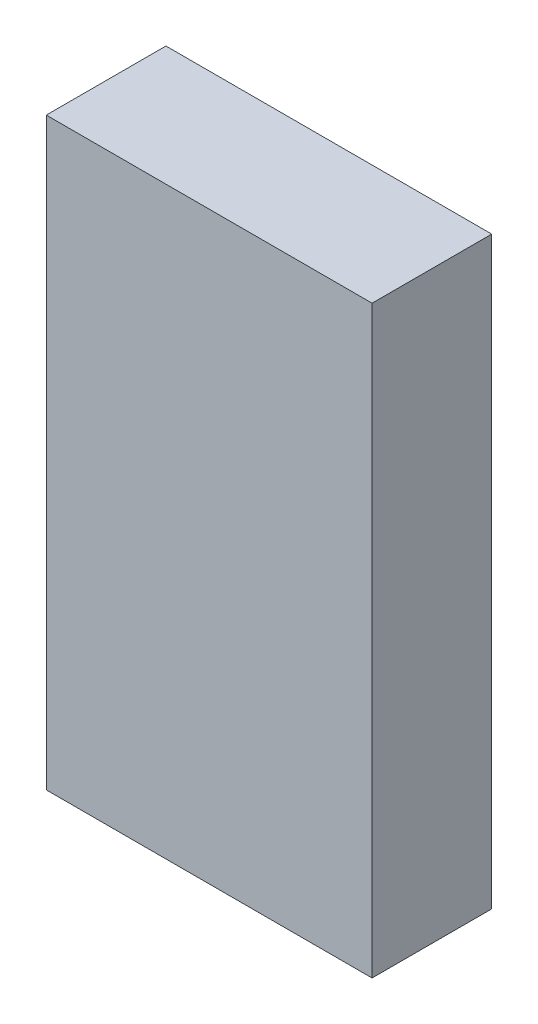
SolidWorks part; units mm, degrees
ref_plane "Спереди" through (0, 0, 0) normal (0, 0, 1) x (1, 0, 0)
ref_plane "Сверху" through (0, 0, 0) normal (0, 1, 0) x (1, 0, 0)
ref_plane "Справа" through (0, 0, 0) normal (1, 0, 0) x (0, 0, -1)
sketch "Эскиз1" plane through (0, 0, 0) normal (0, 0, 1) x (1, 0, 0)
  line L1 (-13.6143, 24.4221) -> (13.6143, 24.4221)
  line L2 (-13.6143, 24.4221) -> (-13.6143, -24.4221)
  line L3 (-13.6143, -24.4221) -> (13.6143, -24.4221)
  line L4 (13.6143, 24.4221) -> (13.6143, -24.4221)
  line L5 (-13.6143, 24.4221) -> (13.6143, -24.4221) construction
  line L6 (-13.6143, -24.4221) -> (13.6143, 24.4221) construction
  point P0 (0, 0)
extrude "Бобышка-Вытянуть1" add sketch "Эскиз1" along normal blind 10
sketch "Эскиз3" plane through (0, 0, 0) normal (0, 0, 1) x (1, 0, 0)
  line L1 (-11.3829, 25.0444) -> (15.8456, 25.0444)
  line L2 (-11.3829, 25.0444) -> (-11.3829, -23.7998)
  line L3 (-11.3829, -23.7998) -> (15.8456, -23.7998)
  line L4 (15.8456, 25.0444) -> (15.8456, -23.7998)
  line L5 (-11.3829, 25.0444) -> (15.8456, -23.7998) construction
  line L6 (-11.3829, -23.7998) -> (15.8456, 25.0444) construction
  point P0 (2.2313, 0.6223)
